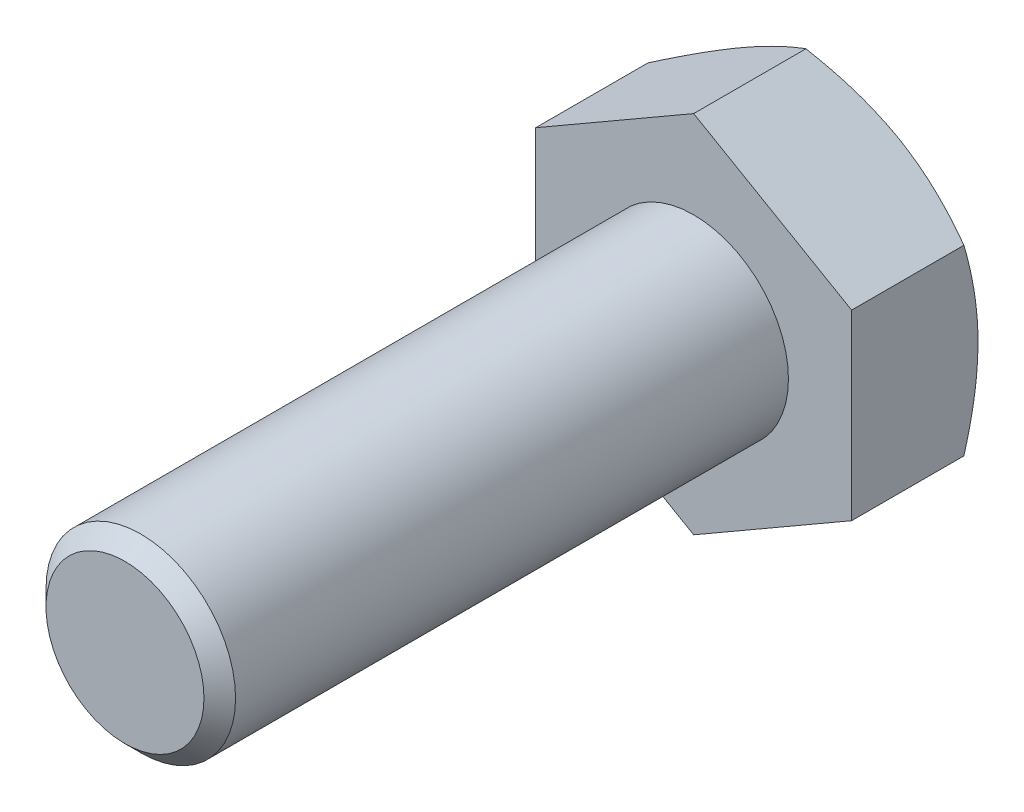
SolidWorks part; units mm, degrees
ref_plane "Front Plane" through (0, 0, 0) normal (0, 0, 1) x (1, 0, 0)
ref_plane "Top Plane" through (0, 0, 0) normal (0, 1, 0) x (1, 0, 0)
ref_plane "Right Plane" through (0, 0, 0) normal (1, 0, 0) x (0, 0, -1)
sketch "Sketch1" plane through (0, 0, 0) normal (0, 0, 1) x (1, 0, 0)
  line L1 (0, -5.7735) -> (5, -2.8868)
  line L2 (5, -2.8868) -> (5, 2.8868)
  line L3 (5, 2.8868) -> (0, 5.7735)
  line L4 (0, 5.7735) -> (-5, 2.8868)
  line L5 (-5, 2.8868) -> (-5, -2.8868)
  line L6 (-5, -2.8868) -> (0, -5.7735)
  circle A0 centre (0, 0) radius 5 construction
  dimension "D1" = 10
extrude "Boss-Extrude1" add sketch "Sketch1" along normal blind 4
sketch "Sketch2" plane through (0, 0, 4) normal (0, 0, 1) x (1, 0, 0)
  circle A0 centre (0, 0) radius 3
  dimension "D1" = 6
extrude "Boss-Extrude2" add sketch "Sketch2" along normal blind 18
sketch "Sketch4" plane through (0, 0, 0) normal (0, 1, 0) x (1, 0, 0)
  line L0 (0, 2.8348) -> (0, -31.1226) construction
sketch "Sketch6" plane through (0, 0, 0) normal (0, 0, -1) x (-1, 0, 0)
  line L0 (-5, 2.8868) -> (0, 5.7735) construction
  circle A0 centre (0, 0) radius 5
extrude "Cut-Extrude1" cut sketch "Sketch6" against normal through all draft 60 flip side to cut
chamfer "Chamfer1" distance 0.5 angle 45 1 edges at (3, 0, 22)
